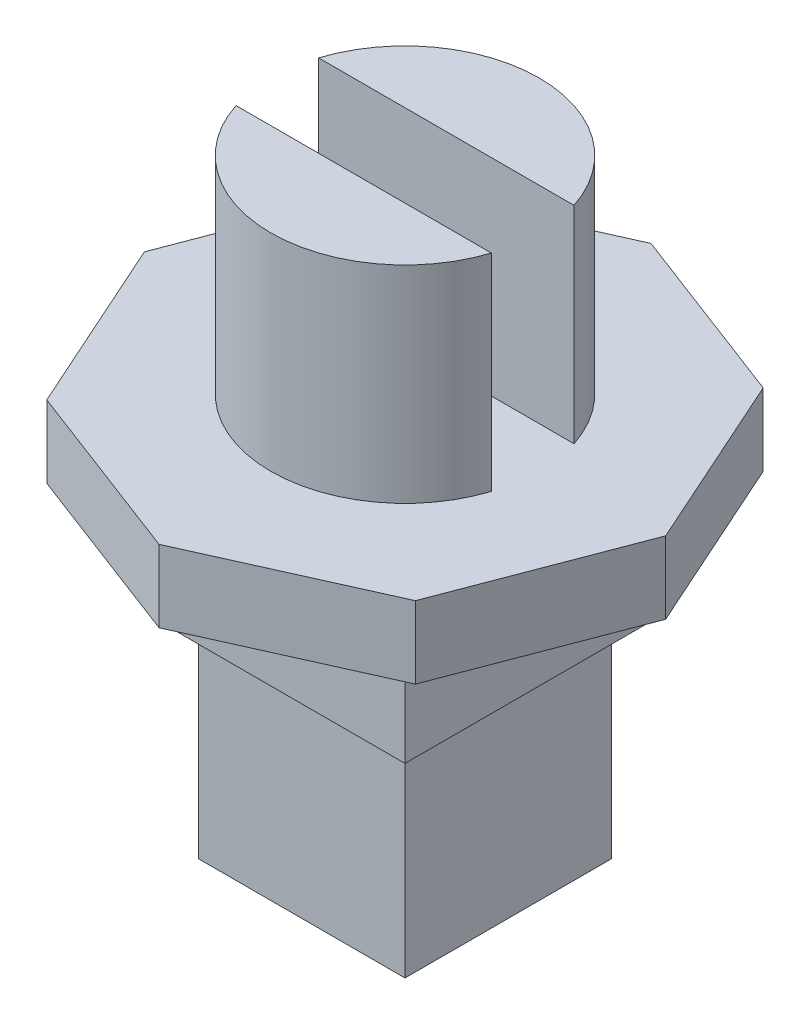
SolidWorks part; units mm, degrees
ref_plane "Front Plane" through (0, 0, 0) normal (0, 0, 1) x (1, 0, 0)
ref_plane "Top Plane" through (0, 0, 0) normal (0, 1, 0) x (1, 0, 0)
ref_plane "Right Plane" through (0, 0, 0) normal (1, 0, 0) x (0, 0, -1)
sketch "Sketch1" plane through (0, 0, 0) normal (0, 1, 0) x (1, 0, 0)
  line L1 (-5, 5) -> (5, 5)
  line L2 (-5, 5) -> (-5, -5)
  line L3 (-5, -5) -> (5, -5)
  line L4 (5, 5) -> (5, -5)
  line L5 (-5, 5) -> (5, -5) construction
  line L6 (-5, -5) -> (5, 5) construction
  point P0 (0, 0)
extrude "Boss-Extrude1" add sketch "Sketch1" against normal blind 10
sketch "Sketch2" plane through (0, 0, 0) normal (0, 1, 0) x (1, 0, 0)
  line L1 (-6, 6) -> (6, 6)
  line L2 (-6, 6) -> (-6, -6)
  line L3 (-6, -6) -> (6, -6)
  line L4 (6, 6) -> (6, -6)
  line L5 (-6, 6) -> (6, -6) construction
  line L6 (-6, -6) -> (6, 6) construction
  point P0 (0, 0)
extrude "Boss-Extrude5" add sketch "Sketch2" along normal blind 6
ref_plane "Plane2" through (0, 6, 0) normal (0, 1, 0) x (1, 0, 0)
sketch "Sketch4" plane through (0, 6, 0) normal (0, 1, 0) x (1, 0, 0)
  line L1 (0.3562, -12.2669) -> (8.9259, -8.4221)
  line L2 (8.9259, -8.4221) -> (12.2669, 0.3562)
  line L3 (12.2669, 0.3562) -> (8.4221, 8.9259)
  line L4 (8.4221, 8.9259) -> (-0.3562, 12.2669)
  line L5 (-0.3562, 12.2669) -> (-8.9259, 8.4221)
  line L6 (-8.9259, 8.4221) -> (-12.2669, -0.3562)
  line L7 (-12.2669, -0.3562) -> (-8.4221, -8.9259)
  line L8 (-8.4221, -8.9259) -> (0.3562, -12.2669)
  circle A0 centre (0, 0) radius 11.3379 construction
extrude "Boss-Extrude6" add sketch "Sketch4" along normal blind 3.5
ref_plane "Plane3" through (0, 9.5, 0) normal (0, 1, 0) x (1, 0, 0)
sketch "Sketch5" plane through (0, 9.5, 0) normal (0, 1, 0) x (1, 0, 0)
  line L0 (9.2, -2) -> (9.2, 2.4)
  line L1 (-9.2, -2) -> (9.2, -2)
  line L2 (-9.2, 2.4) -> (9.2, 2.4)
  line L3 (0, -10.725) -> (0, 10.725) construction
  line L4 (-9.2, -2) -> (-9.2, 2.4)
  point P10 (0, 2.4)
  point P11 (0, -2)
sketch "Sketch8" plane through (0, 9.5, 0) normal (0, 1, 0) x (1, 0, 0)
  line L0 (-6.1847, 2) -> (6.1847, 2)
  line L1 (6.1847, -2) -> (-6.1847, -2)
  arc A0 (-6.1847, -2) -> (6.1847, -2) centre (0, 0) ccw
  arc A1 (6.1847, 2) -> (-6.1847, 2) centre (0, 0) ccw
extrude "Boss-Extrude11" add sketch "Sketch8" along normal blind 10 contours L0 A1 | L1 A0
